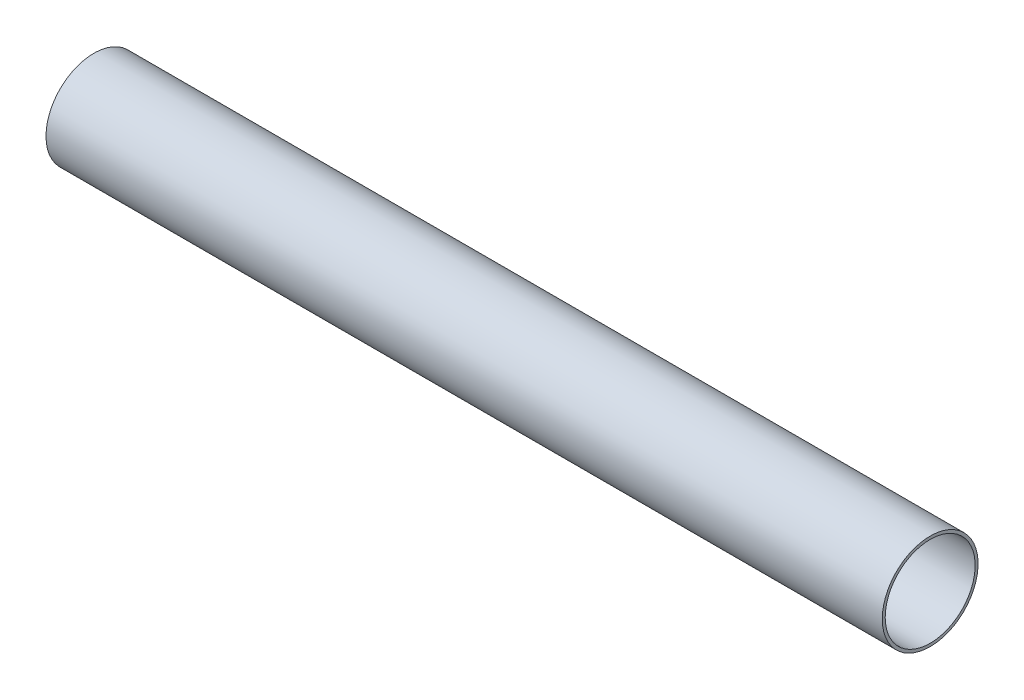
SolidWorks part; units mm, degrees
material "Copper"
ref_plane "Front" through (0, 0, 0) normal (0, 0, 1) x (1, 0, 0)
ref_plane "Top" through (0, 0, 0) normal (0, 1, 0) x (1, 0, 0)
ref_plane "Right" through (0, 0, 0) normal (1, 0, 0) x (0, 0, -1)
sketch "Sketch1" plane through (0, 0, 0) normal (1, 0, 0) x (0, 0, -1)
  circle A0 centre (0, 0) radius 17.4625
  circle A1 centre (0, 0) radius 16.3957
  point P4 (17.4625, 0)
  point P5 (16.3957, 0)
  dimension "OD" = 34.925
  dimension "ID" = 32.7914
  dimension "Wall" = 1.0668
extrude "Extrude1" add sketch "Sketch1" along normal mid plane 304.8
sketch "Sketch2" plane through (0, 0, 0) normal (0, 0, 1) x (1, 0, 0)
  line L0 (-152.4, 0) -> (152.4, 0) construction
  line L1 (-152.4, 17.4625) -> (-152.4, -17.4625) construction
